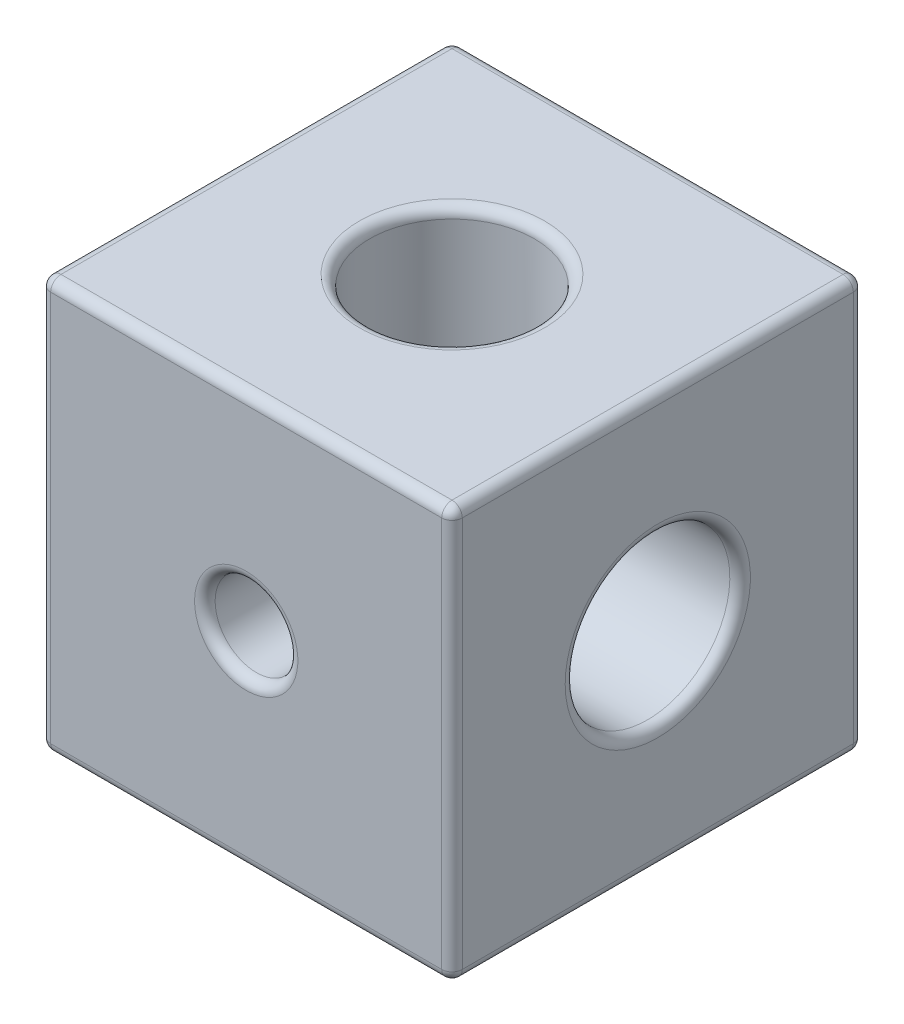
SolidWorks part; units mm, degrees
ref_plane "Front Plane" through (0, 0, 0) normal (0, 0, 1) x (1, 0, 0)
ref_plane "Top Plane" through (0, 0, 0) normal (0, 1, 0) x (1, 0, 0)
ref_plane "Right Plane" through (0, 0, 0) normal (1, 0, 0) x (0, 0, -1)
sketch "Sketch1" plane through (0, 0, 0) normal (0, 0, 1) x (1, 0, 0)
  line L1 (0, 0) -> (25.4, 0)
  line L2 (0, 0) -> (0, 25.4)
  line L3 (0, 25.4) -> (25.4, 25.4)
  line L4 (25.4, 0) -> (25.4, 25.4)
  dimension "D1" = 25.4
  dimension "D2" = 25.4
extrude "Boss-Extrude1" add sketch "Sketch1" along normal blind 25.4
hole_wizard "1/4-20 Tapped Hole1" positions "3DSketch3" profile "Sketch6" tap size "1/4-20" standard "ANSI Inch" end condition through all
sketch3d "3DSketch3"
  line L1 (12.7, 25.4, 25.4) -> (12.7, 0, 25.4) construction
  line L2 (25.4, 25.4, 25.4) -> (0, 25.4, 25.4) construction
  line L3 (0, 0, 25.4) -> (25.4, 0, 25.4) construction
  line L5 (25.4, 25.4, 12.7) -> (25.4, 0, 12.7) construction
  line L6 (25.4, 25.4, 25.4) -> (25.4, 25.4, 0) construction
  line L7 (25.4, 0, 25.4) -> (25.4, 0, 0) construction
  line L9 (0, 25.4, 12.7) -> (25.4, 25.4, 12.7) construction
  line L10 (0, 25.4, 25.4) -> (0, 25.4, 0) construction
  point P0 (12.7, 12.7, 25.4)
  point P2 (25.4, 12.7, 12.7)
  point P4 (12.7, 25.4, 12.7)
cosmetic thread "Hole Thread1" parameters "D2"=6.35
cosmetic thread "Hole Thread2" parameters "D2"=6.35
cosmetic thread "Hole Thread3" parameters "D2"=6.35
sketch "Sketch6" plane through (12.7, 12.7, 25.4) normal (1, 0, 0) x (0, -1, 0)
  line L0 (0, 0) -> (0, 25.4)
  line L1 (0, 25.4) -> (2.5527, 25.4)
  line L2 (2.5527, 25.4) -> (2.5527, 0)
  line L5 (2.5527, 0) -> (0, 0)
  line L11 (0, -6.35) -> (0, 107.95) construction
  dimension "Thru Tap Drill Dia." = 5.1054
  dimension "Thru Tap Drill Depth" = 25.4
sketch "Sketch7" plane through (25.4, 0, 0) normal (1, 0, 0) x (0, 0, -1)
  circle A0 centre (-12.7, 12.7) radius 5.08
  dimension "D1" = 10.16
extrude "Cut-Extrude1" cut sketch "Sketch7" against normal blind 12.7
sketch "Sketch8" plane through (0, 0, 0) normal (0, 0, -1) x (-1, 0, 0)
  circle A0 centre (-12.7, 12.7) radius 5.08
  dimension "D1" = 10.16
extrude "Cut-Extrude2" cut sketch "Sketch8" against normal blind 12.7
sketch "Sketch10" plane through (0, 25.4, 0) normal (0, 1, 0) x (1, 0, 0)
  circle A0 centre (12.7, -12.7) radius 5.08
  dimension "D1" = 10.16
extrude "Cut-Extrude3" cut sketch "Sketch10" against normal blind 12.7
fillet "Fillet1" radius 0.635 18 edges at (0, 12.7, 10.1473) (0, 0, 12.7) (12.7, 0, 15.2527) (12.7, 0, 0) (0, 12.7, 0) (7.62, 12.7, 0) (25.4, 0, 12.7) (25.4, 12.7, 0) (25.4, 12.7, 7.62) (15.2527, 12.7, 25.4) (25.4, 12.7, 25.4) (12.7, 0, 25.4) (0, 12.7, 25.4) (25.4, 25.4, 12.7) (12.7, 25.4, 25.4) (0, 25.4, 12.7) (12.7, 25.4, 0) (12.7, 25.4, 17.78)
